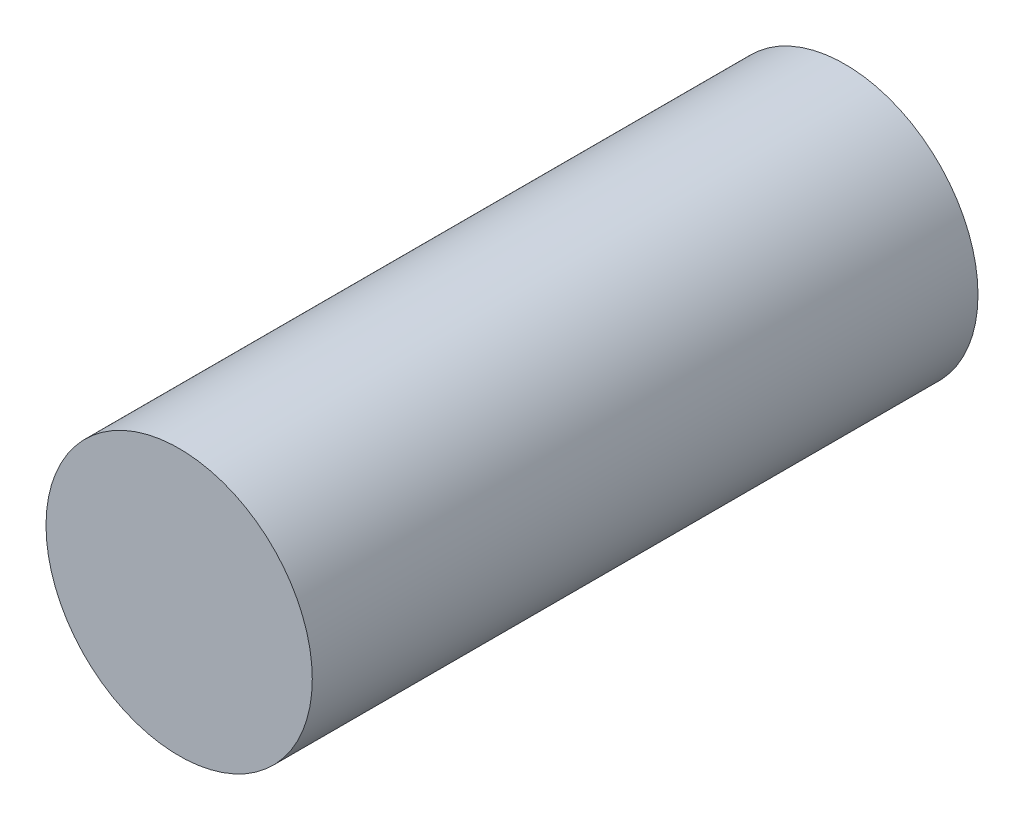
SolidWorks part; units mm, degrees
ref_plane "Front Plane" through (0, 0, 0) normal (0, 0, 1) x (1, 0, 0)
ref_plane "Top Plane" through (0, 0, 0) normal (0, 1, 0) x (1, 0, 0)
ref_plane "Right Plane" through (0, 0, 0) normal (1, 0, 0) x (0, 0, -1)
sketch "Sketch1" plane through (0, 0, 0) normal (0, 0, 1) x (1, 0, 0)
  circle A0 centre (-53.0012, 15.9004) radius 30
sketch "Sketch2" plane through (0, 0, 0) normal (0, 0, 1) x (1, 0, 0)
  circle A0 centre (-53.0012, 15.9004) radius 30
extrude "Boss-Extrude1" add sketch "Sketch2" along normal blind 150
